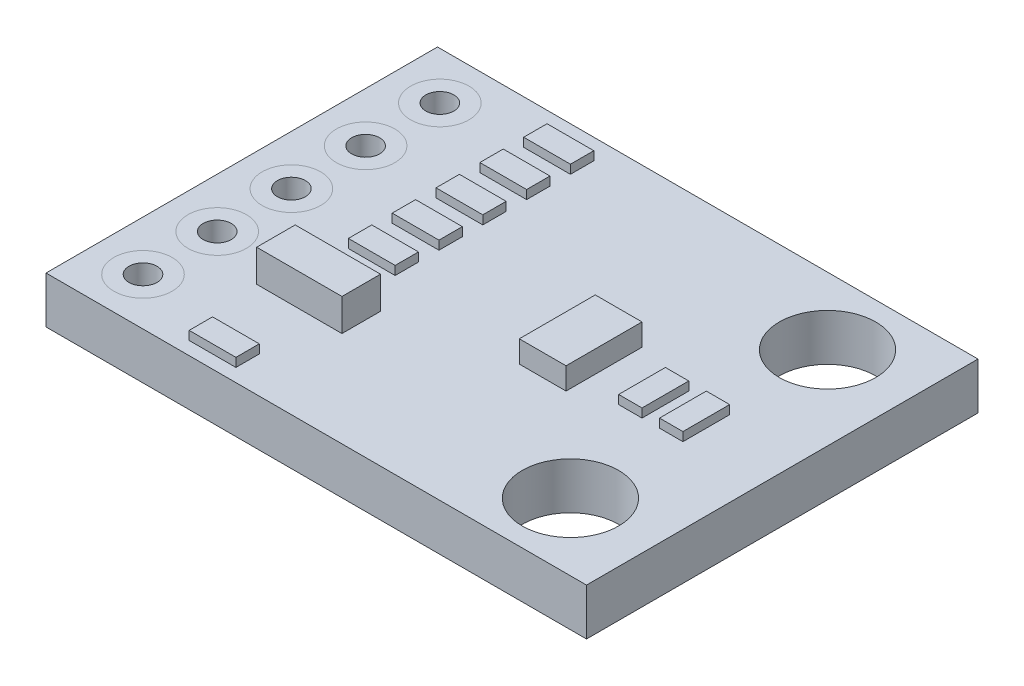
SolidWorks part; units mm, degrees
ref_plane "Front Plane" through (0, 0, 0) normal (0, 0, 1) x (1, 0, 0)
ref_plane "Top Plane" through (0, 0, 0) normal (0, 1, 0) x (1, 0, 0)
ref_plane "Right Plane" through (0, 0, 0) normal (1, 0, 0) x (0, 0, -1)
sketch "Sketch2" plane through (0, 0, 0) normal (0, 1, 0) x (1, 0, 0)
  line L0 (-9.25, 6.7) -> (9.25, -6.7) construction
  line L1 (-9.25, 6.7) -> (9.25, 6.7)
  line L2 (-9.25, 6.7) -> (-9.25, -6.7)
  line L3 (-9.25, -6.7) -> (9.25, -6.7)
  line L4 (9.25, 6.7) -> (9.25, -6.7)
  dimension "D1" = 13.4
  dimension "D2" = 18.5
extrude "Boss-Extrude1" add sketch "Sketch2" along normal blind 1.6
sketch "Sketch3" plane through (0, 1.6, 0) normal (0, 1, 0) x (1, 0, 0)
  line L0 (-7.55, 5.08) -> (-7.55, 2.54) construction
  line L1 (-7.55, 2.54) -> (-7.55, 0) construction
  line L2 (-7.55, 0) -> (-7.55, -2.54) construction
  line L3 (-7.55, -2.54) -> (-7.55, -5.08) construction
  line L4 (-9.25, 6.7) -> (-9.25, -6.7) construction
  line L5 (6.4, 4.4) -> (6.4, -4.4) construction
  line L6 (9.25, -6.7) -> (9.25, 6.7) construction
  line L7 (0, 0) -> (6.4, 0) construction
  circle A0 centre (-7.55, 5.08) radius 0.48
  circle A1 centre (-7.55, 2.54) radius 0.48
  circle A2 centre (-7.55, 0) radius 0.48
  circle A3 centre (-7.55, -2.54) radius 0.48
  circle A4 centre (-7.55, -5.08) radius 0.48
  circle A5 centre (6.4, 4.4) radius 1.65
  circle A6 centre (6.4, -4.4) radius 1.65
  dimension "D1" = 2.54
  dimension "D2" = 0.96
  dimension "D4" = 3.3
  dimension "D3" = 1.7
  dimension "D5" = 8.8
  dimension "D6" = 2.85
extrude "Cut-Extrude1" cut sketch "Sketch3" against normal through all both and the other way through all
sketch "Sketch5" plane through (0, 1.6, 0) normal (0, 1, 0) x (1, 0, 0)
  circle A0 centre (-7.55, 5.08) radius 1
  circle A1 centre (-7.55, 2.54) radius 1
  circle A2 centre (-7.55, 0) radius 1
  circle A3 centre (-7.55, -2.54) radius 1
  circle A4 centre (-7.55, -5.08) radius 1
  dimension "D1" = 2
split line "Split Line1"
sketch "Sketch6" plane through (0, 1.6, 0) normal (0, 1, 0) x (1, 0, 0)
  line L0 (-9.25, 6.7) -> (-9.25, -6.7) construction
  line L1 (-4.8, 6) -> (-3.2, 6)
  line L2 (-4.8, 6) -> (-4.8, 5.2)
  line L3 (-4.8, 5.2) -> (-3.2, 5.2)
  line L4 (-3.2, 6) -> (-3.2, 5.2)
  line L5 (-4.8, 4.5) -> (-3.2, 4.5)
  line L6 (-4.8, 4.5) -> (-4.8, 3.7)
  line L7 (-4.8, 3.7) -> (-3.2, 3.7)
  line L8 (-3.2, 4.5) -> (-3.2, 3.7)
  line L9 (-4.8, 3) -> (-3.2, 3)
  line L10 (-4.8, 3) -> (-4.8, 2.2)
  line L11 (-4.8, 2.2) -> (-3.2, 2.2)
  line L12 (-3.2, 3) -> (-3.2, 2.2)
  line L13 (-4.8, 1.5) -> (-3.2, 1.5)
  line L14 (-4.8, 1.5) -> (-4.8, 0.7)
  line L15 (-4.8, 0.7) -> (-3.2, 0.7)
  line L16 (-3.2, 1.5) -> (-3.2, 0.7)
  line L17 (-4.8, 0) -> (-3.2, 0)
  line L18 (-4.8, 0) -> (-4.8, -0.8)
  line L19 (-4.8, -0.8) -> (-3.2, -0.8)
  line L20 (-3.2, 0) -> (-3.2, -0.8)
  line L21 (-4.8, -5.45) -> (-3.2, -5.45)
  line L22 (-4.8, -5.45) -> (-4.8, -6.25)
  line L23 (-4.8, -6.25) -> (-3.2, -6.25)
  line L24 (-3.2, -5.45) -> (-3.2, -6.25)
  line L25 (6.65, 0.8) -> (5.85, 0.8)
  line L26 (6.65, 0.8) -> (6.65, -0.8)
  line L27 (6.65, -0.8) -> (5.85, -0.8)
  line L28 (5.85, 0.8) -> (5.85, -0.8)
  line L29 (5.25, 0.8) -> (4.45, 0.8)
  line L30 (5.25, 0.8) -> (5.25, -0.8)
  line L31 (5.25, -0.8) -> (4.45, -0.8)
  line L32 (4.45, 0.8) -> (4.45, -0.8)
  line L33 (9.25, 6.7) -> (-9.25, 6.7) construction
  line L34 (-9.25, -6.7) -> (9.25, -6.7) construction
  line L35 (-3.2, 6) -> (-3.2, 6.7) construction
  line L36 (-3.2, 5.2) -> (-3.2, 4.5) construction
  line L37 (-3.2, 3.7) -> (-3.2, 3) construction
  line L38 (-3.2, 2.2) -> (-3.2, 1.5) construction
  line L39 (-3.2, 0) -> (-3.2, 0.7) construction
  line L40 (9.25, -6.7) -> (9.25, 6.7) construction
  line L41 (4.45, 0) -> (0, 0) construction
  dimension "D1" = 1.6
  dimension "D2" = 0.8
  dimension "D3" = 4.45
  dimension "D4" = 0.7
  dimension "D5" = 0.45
  dimension "D6" = 2.6
  dimension "D7" = 0.6
extrude "Boss-Extrude2" add sketch "Sketch6" along normal blind 0.3
sketch "Sketch7" plane through (0, 1.6, 0) normal (0, 1, 0) x (1, 0, 0)
  line L0 (-9.25, 6.7) -> (-9.25, -6.7) construction
  line L5 (-5.31, -2.11) -> (-2.39, -2.11)
  line L6 (-5.31, -2.11) -> (-5.31, -3.43)
  line L7 (-5.31, -3.43) -> (-2.39, -3.43)
  line L8 (-2.39, -2.11) -> (-2.39, -3.43)
  line L9 (-9.25, -6.7) -> (9.25, -6.7) construction
  dimension "D1" = 2.92
  dimension "D2" = 1.32
  dimension "D3" = 3.94
  dimension "D4" = 3.27
extrude "Boss-Extrude3" add sketch "Sketch7" along normal blind 1.1
sketch "Sketch8" plane through (0, 1.6, 0) normal (0, 1, 0) x (1, 0, 0)
  line L0 (-9.25, -6.7) -> (9.25, -6.7) construction
  line L1 (1.55, 1.3) -> (3.15, 1.3)
  line L2 (1.55, 1.3) -> (1.55, -1.3)
  line L3 (1.55, -1.3) -> (3.15, -1.3)
  line L4 (3.15, 1.3) -> (3.15, -1.3)
  line L5 (9.25, -6.7) -> (9.25, 6.7) construction
  dimension "D1" = 2.6
  dimension "D2" = 1.6
  dimension "D3" = 5.4
  dimension "D4" = 6.1
extrude "Boss-Extrude4" add sketch "Sketch8" along normal blind 0.75
